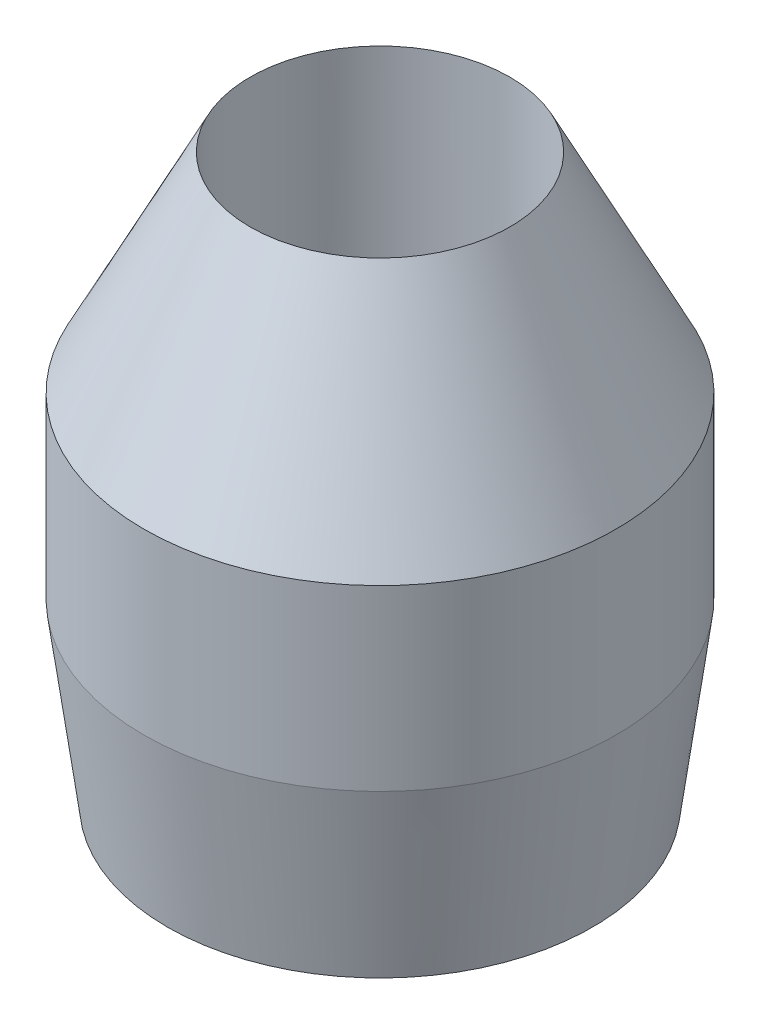
SolidWorks part; units mm, degrees
material "ABS"
ref_plane "Front Plane" through (0, 0, 0) normal (0, 0, 1) x (1, 0, 0)
ref_plane "Top Plane" through (0, 0, 0) normal (0, 1, 0) x (1, 0, 0)
ref_plane "Right Plane" through (0, 0, 0) normal (1, 0, 0) x (0, 0, -1)
sketch "Sketch1" plane through (0, 0, 0) normal (0, 1, 0) x (1, 0, 0)
  circle A0 centre (0, 0) radius 10
  dimension "D1" = 20
extrude "Boss-Extrude1" add sketch "Sketch1" along normal blind 15.1
sketch "Sketch2" plane through (0, 0, 0) normal (0, -1, 0) x (-1, 0, 0)
  circle A0 centre (0, 0) radius 8.25
  dimension "D1" = 16.5
extrude "Cut-Extrude1" cut sketch "Sketch2" against normal blind 7
sketch "Sketch3" plane through (0, 7, 0) normal (0, -1, 0) x (1, 0, 0)
  circle A0 centre (0, 0) radius 6.35
  dimension "D1" = 12.7
extrude "Cut-Extrude2" cut sketch "Sketch3" against normal blind 8.1
sketch "Sketch7" plane through (0, 15.1, 0) normal (0, 1, 0) x (1, 0, 0)
  circle A0 centre (0, 0) radius 10
extrude "Boss-Extrude2" add sketch "Sketch7" along normal blind 10 draft 27
sketch "Sketch8" plane through (0, 25.1, 0) normal (0, 1, 0) x (1, 0, 0)
  circle A0 centre (0, 0) radius 5.5
  dimension "D1" = 11
extrude "Cut-Extrude3" cut sketch "Sketch8" against normal blind 10 contours A0
sketch "Sketch9" plane through (0, 0, 0) normal (0, 0, 1) x (1, 0, 0)
  line L0 (0, -5.3541) -> (0, 29.1689) construction
  line L7 (10, 0) -> (10, 7.55)
  line L9 (10, 0) -> (10, 15.1) construction
  line L10 (10, 7.55) -> (9, 0)
  line L11 (-10, 0) -> (10, 0) construction
  line L12 (9, 0) -> (10, 0)
  dimension "D1" = 1
revolve "Cut-Revolve1" cut sketch "Sketch9" angle 360 about L0
